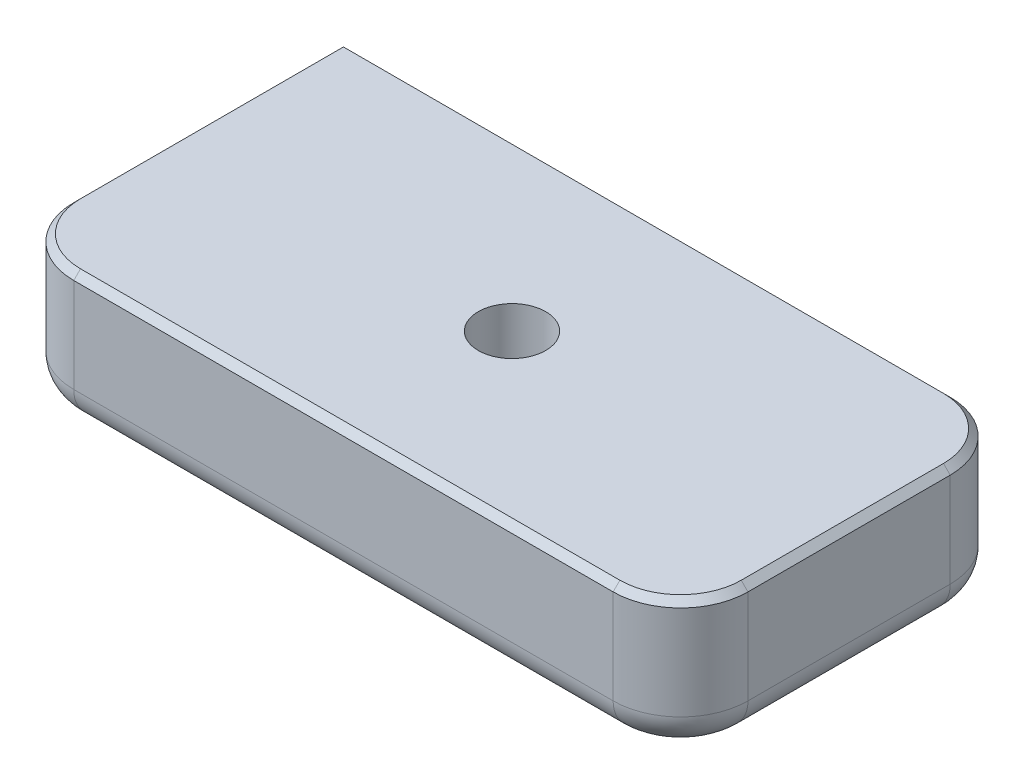
SolidWorks part; units mm, degrees
ref_plane "Front Plane" through (0, 0, 0) normal (0, 0, 1) x (1, 0, 0)
ref_plane "Top Plane" through (0, 0, 0) normal (0, 1, 0) x (1, 0, 0)
ref_plane "Right Plane" through (0, 0, 0) normal (1, 0, 0) x (0, 0, -1)
sketch "Sketch1" plane through (0, 0, 0) normal (0, 1, 0) x (1, 0, 0)
  line L1 (-50, 25) -> (50, 25)
  line L2 (-50, 25) -> (-50, -25)
  line L3 (-50, -25) -> (50, -25)
  line L4 (50, 25) -> (50, -25)
  line L5 (0, -25) -> (0, 25) construction
  line L6 (-50, 0) -> (50, 0) construction
  point P0 (0, 0)
  dimension "D1" = 100
  dimension "D2" = 50
extrude "Boss-Extrude1" add sketch "Sketch1" along normal blind 20
sketch "Sketch2" plane through (0, 20, 0) normal (0, 1, 0) x (1, 0, 0)
  circle A0 centre (0, 0) radius 15
  dimension "D1" = 30
extrude "Cut-Extrude1" cut sketch "Sketch2" against normal blind 20
fillet "Fillet1" radius 10 3 edges at (50, 10, -25) (50, 10, 25) (-50, 10, 25)
chamfer "Chamfer1" distance 1 angle 45 7 edges at (-5, 20, -25) (47.0711, 20, -22.0711) (-50, 20, -5) (50, 20, 0) (-47.0711, 20, 22.0711) (47.0711, 20, 22.0711) (0, 20, 25)
other "Move Face1" face at (0, 0, 15) parameters "D1"=10
fillet "Fillet2" radius 5 7 edges at (-50, 0, -5) (-47.0711, 0, 22.0711) (-5, 0, -25) (47.0711, 0, -22.0711) (50, 0, 0) (47.0711, 0, 22.0711) (0, 0, 25)
